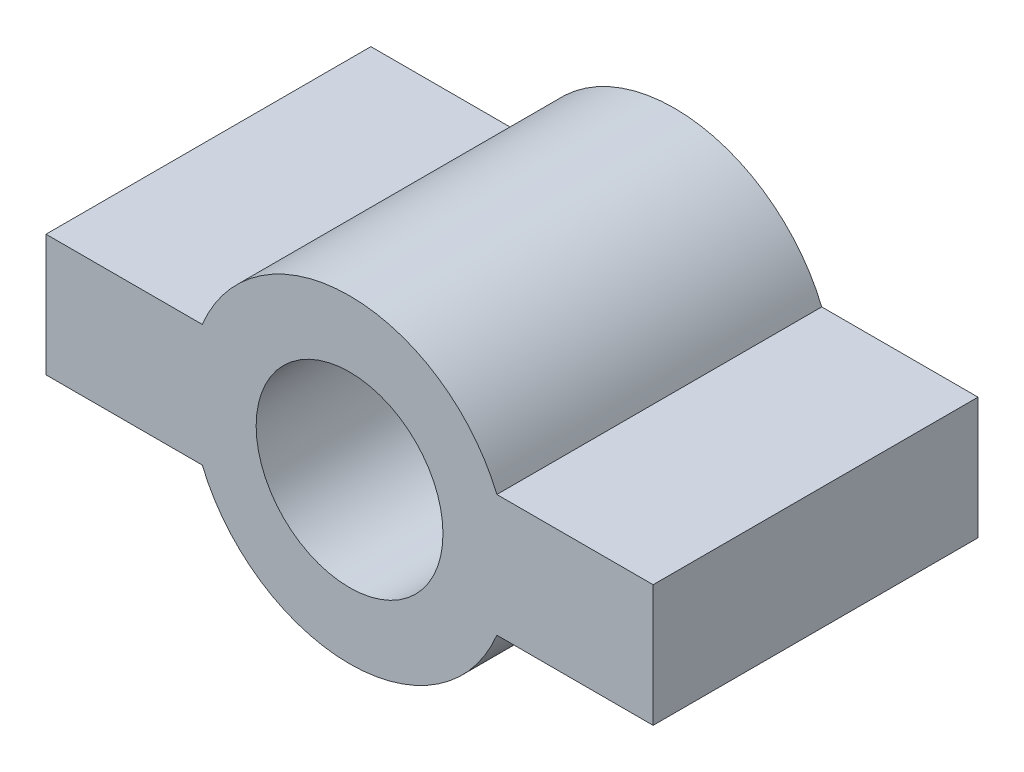
SolidWorks part; units mm, degrees
ref_plane "Alzado" through (0, 0, 0) normal (0, 0, 1) x (1, 0, 0)
ref_plane "Planta" through (0, 0, 0) normal (0, 1, 0) x (1, 0, 0)
ref_plane "Vista lateral" through (0, 0, 0) normal (1, 0, 0) x (0, 0, -1)
sketch "Croquis1" plane through (0, 0, 0) normal (0, 0, 1) x (1, 0, 0)
  line L0 (3.6271, 1.5) -> (7.475, 1.5)
  line L1 (7.475, 1.5) -> (7.475, -1.5)
  line L2 (7.475, -1.5) -> (3.6271, -1.5)
  line L3 (0, 0) -> (0, 8.465) construction
  line L4 (-7.475, -1.5) -> (-3.6271, -1.5)
  line L5 (-7.475, 1.5) -> (-7.475, -1.5)
  line L6 (-3.6271, 1.5) -> (-7.475, 1.5)
  arc A0 (-3.6271, -1.5) -> (3.6271, -1.5) centre (0, 0) ccw
  circle A1 centre (0, 0) radius 2.3
  arc A2 (3.6271, 1.5) -> (-3.6271, 1.5) centre (0, 0) ccw
  point P6 (7.475, 0)
  dimension "D2" = 7.85
  dimension "D3" = 4.6
  dimension "D1" = 3
  dimension "D4" = 14.95
extrude "Saliente-Extruir1" add sketch "Croquis1" against normal blind 8
